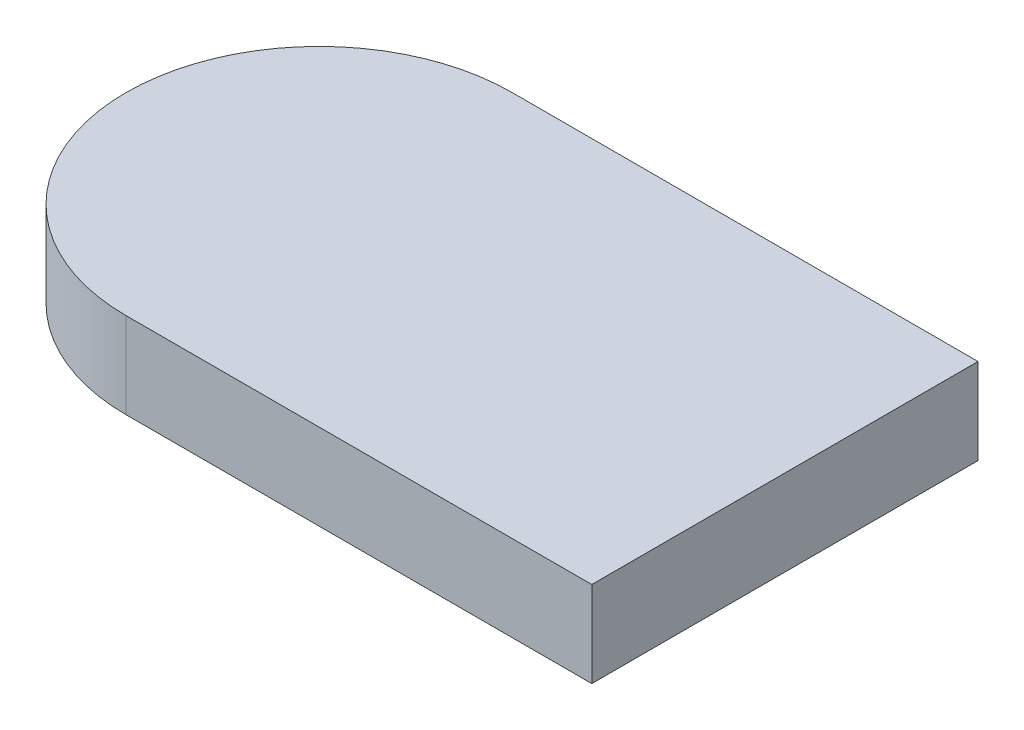
SolidWorks part; units mm, degrees
ref_plane "Front Plane" through (0, 0, 0) normal (0, 0, 1) x (1, 0, 0)
ref_plane "Top Plane" through (0, 0, 0) normal (0, 1, 0) x (1, 0, 0)
ref_plane "Right Plane" through (0, 0, 0) normal (1, 0, 0) x (0, 0, -1)
sketch "Sketch1" plane through (0, 0, 0) normal (0, 1, 0) x (1, 0, 0)
  line L0 (0, 90) -> (217.08, 90)
  line L1 (217.08, 90) -> (217.08, -90)
  line L2 (217.08, -90) -> (0, -90)
  arc A0 (0, -90) -> (0, 90) centre (0, 0) cw
  dimension "D1" = 217.08
  dimension "D2" = 180
extrude "Boss-Extrude1" add sketch "Sketch1" along normal blind 40
